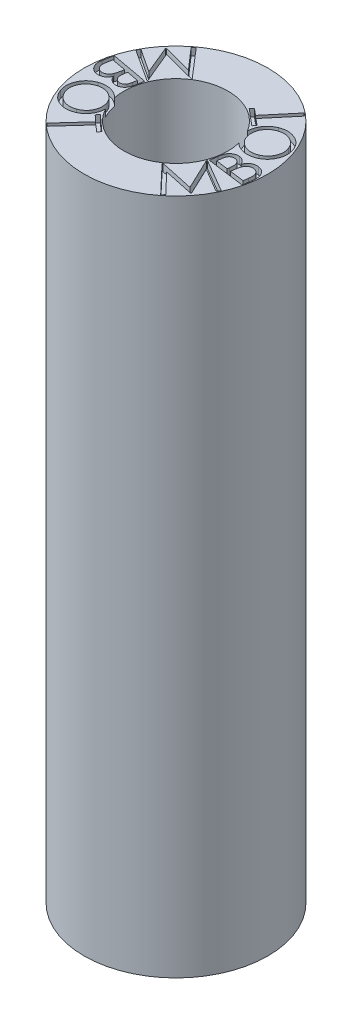
SolidWorks part; units mm, degrees
ref_plane "Front Plane" through (0, 0, 0) normal (0, 0, 1) x (1, 0, 0)
ref_plane "Top Plane" through (0, 0, 0) normal (0, 1, 0) x (1, 0, 0)
ref_plane "Right Plane" through (0, 0, 0) normal (1, 0, 0) x (0, 0, -1)
sketch "Sketch1" plane through (0, 0, 0) normal (0, 1, 0) x (1, 0, 0)
  circle A0 centre (0, 0) radius 2.15
  circle A1 centre (0, 0) radius 3.8
  dimension "D1" = 4.3
  dimension "D2" = 7.6
extrude "Boss-Extrude1" add sketch "Sketch1" along normal blind 28
sketch "Sketch5" plane through (0, 28, 0) normal (0, 1, 0) x (1, 0, 0)
  text T0 "MBOT    MBOT" font "Century Gothic" height in points 6
extrude "Cut-Extrude1" cut sketch "Sketch5" against normal blind 0.3
